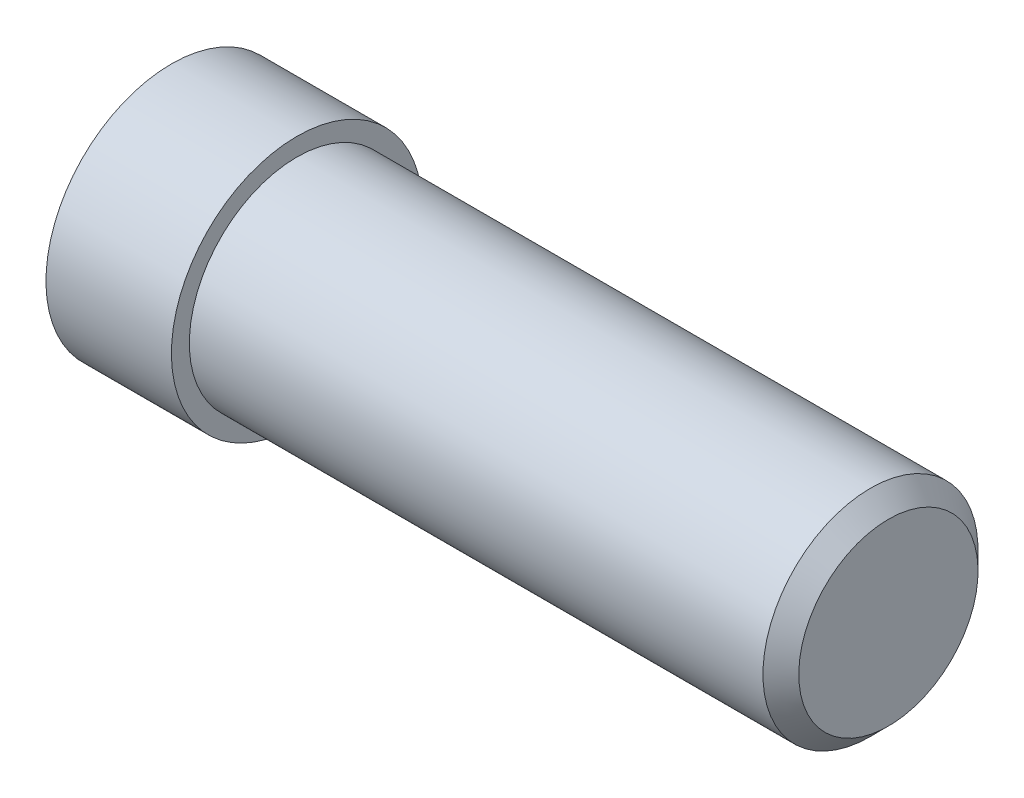
SolidWorks part; units mm, degrees
ref_plane "Front Plane" through (0, 0, 0) normal (0, 0, 1) x (1, 0, 0)
ref_plane "Top Plane" through (0, 0, 0) normal (0, 1, 0) x (1, 0, 0)
ref_plane "Right Plane" through (0, 0, 0) normal (1, 0, 0) x (0, 0, -1)
sketch "Sketch1" plane through (0, 0, 0) normal (0, 0, 1) x (1, 0, 0)
  line L0 (0, 0) -> (-40, 0)
  line L1 (-40, 0) -> (-40, 7)
  line L2 (-40, 7) -> (-33, 7)
  line L3 (-33, 7) -> (-33, 6)
  line L4 (-33, 6) -> (0, 6)
  line L5 (0, 6) -> (0, 0)
  dimension "D1" = 7
  dimension "D2" = 6
  dimension "D3" = 33
revolve "Revolve1" add sketch "Sketch1" angle 360 about L0
chamfer "Chamfer1" distance 1 angle 45 1 edges at (0, 6, 0)
